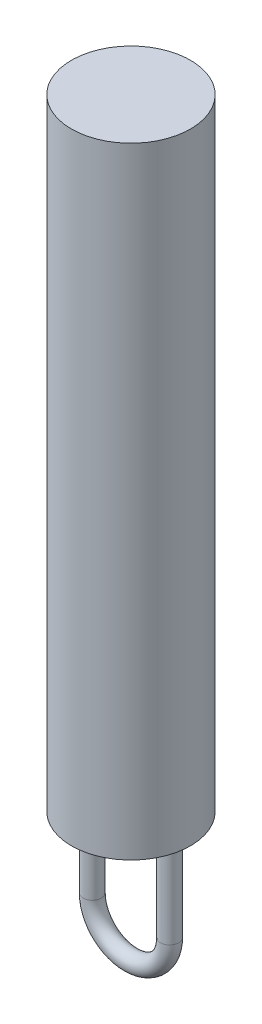
SolidWorks part; units mm, degrees
ref_plane "Front Plane" through (0, 0, 0) normal (0, 0, 1) x (1, 0, 0)
ref_plane "Top Plane" through (0, 0, 0) normal (0, 1, 0) x (1, 0, 0)
ref_plane "Right Plane" through (0, 0, 0) normal (1, 0, 0) x (0, 0, -1)
ref_plane "PLN_TOP" through (0, 132.4, 0) normal (0, 1, 0) x (1, 0, 0)
sketch "Sketch1" plane through (0, 0, 0) normal (0, 1, 0) x (1, 0, 0)
  circle A0 centre (0, 0) radius 12.7
  dimension "D1" = 25.4
extrude "Boss-Extrude1" add sketch "Sketch1" along normal up to surface (132.4 mm away) up to plane "PLN_TOP"
sketch "Sketch2" plane through (0, 0, 0) normal (0, -1, 0) x (1, 0, 0)
  line L0 (-8.25, 0) -> (8.25, 0) construction
  circle A0 centre (8.25, 0) radius 1.95
  point P3 (6.3, 0)
  point P4 (0, 0)
  dimension "D1" = 3.9
  dimension "D2" = 6.3
sketch "Sketch3" plane through (0, 0, 0) normal (0, 0, 1) x (1, 0, 0)
  line L0 (8.25, 0) -> (8.25, -19.15)
  line L1 (8.25, -19.15) -> (-8.25, -19.15) construction
  line L2 (-8.25, -19.15) -> (-8.25, 0)
  line L3 (-8.25, 0) -> (8.25, 0) construction
  line L4 (0, 0) -> (0, -19.15) construction
  arc A0 (-8.25, -19.15) -> (8.25, -19.15) centre (0, -19.15) ccw
  point P8 (0, -25.4)
  point P13 (0, -27.4)
  dimension "D1" = 2
  dimension "D2" = 25.4
sweep "Sweep1" add profiles "Sketch2" path "Sketch3"
